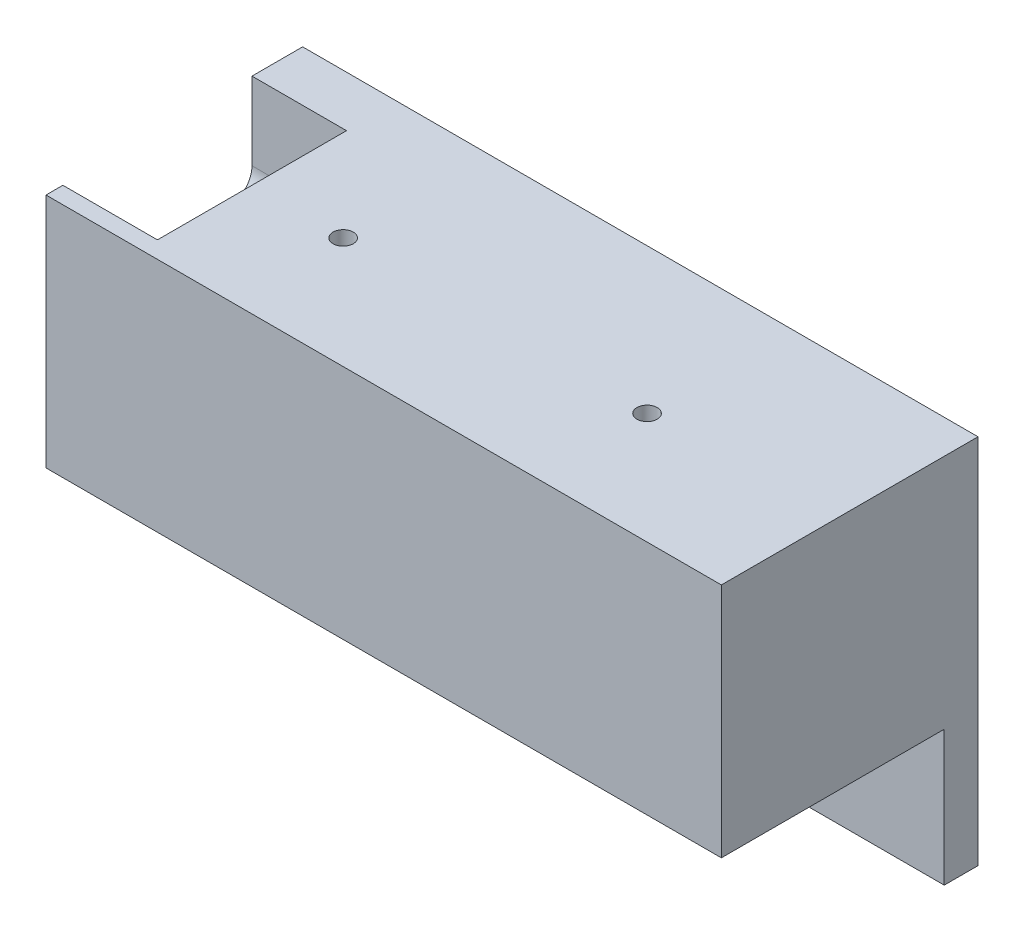
SolidWorks part; units mm, degrees
ref_plane "Ebene vorne" through (0, 0, 0) normal (0, 0, 1) x (1, 0, 0)
ref_plane "Ebene oben" through (0, 0, 0) normal (0, 1, 0) x (1, 0, 0)
ref_plane "Ebene rechts" through (0, 0, 0) normal (1, 0, 0) x (0, 0, -1)
sketch "Skizze1" plane through (0, 0, 0) normal (0, 0, 1) x (1, 0, 0)
  line L1 (-50, 27.5) -> (50, 27.5)
  line L2 (-50, 27.5) -> (-50, -27.5)
  line L3 (-50, -27.5) -> (50, -27.5)
  line L4 (50, 27.5) -> (50, -27.5)
  point P4 (0, 27.5)
  point P6 (50, 0)
  dimension "D1" = 100
  dimension "D2" = 55
extrude "Aufsatz-Linear austragen1" add sketch "Skizze1" along normal blind 38
sketch "Skizze2" plane through (0, 0, 38) normal (0, 0, 1) x (1, 0, 0)
  line L0 (50, -27.5) -> (50, 27.5) construction
  line L1 (-50, -27.5) -> (50, -27.5)
  line L2 (-50, -27.5) -> (-50, -7.5)
  line L3 (-50, -7.5) -> (50, -7.5)
  line L4 (50, -27.5) -> (50, -7.5)
  line L5 (50, 27.5) -> (-50, 27.5) construction
  dimension "D1" = 35
extrude "Schnitt-Linear austragen1" cut sketch "Skizze2" against normal blind 33
sketch "Skizze4" plane through (0, 0, 5) normal (0, 0, 1) x (1, 0, 0)
  line L0 (-50, -27.5) -> (50, -27.5) construction
  circle A0 centre (-10, -19.5) radius 1.5
  circle A1 centre (10, -19.5) radius 1.5
  dimension "D1" = 3
  dimension "D2" = 20
  dimension "D3" = 10
  dimension "D4" = 8
extrude "Schnitt-Linear austragen2" cut sketch "Skizze4" against normal through all
sketch "Skizze5" plane through (0, -7.5, 0) normal (0, -1, 0) x (1, 0, 0)
  line L0 (-50, 5) -> (-50, 38) construction
  line L1 (-46, 35.5) -> (46, 35.5)
  line L2 (-46, 35.5) -> (-46, 7.5)
  line L3 (-46, 7.5) -> (46, 7.5)
  line L4 (46, 35.5) -> (46, 7.5)
  point P4 (-46, 21.5)
  point P7 (-50, 21.5)
  point P8 (0, 35.5)
  dimension "D1" = 28
  dimension "D2" = 92
extrude "Schnitt-Linear austragen3" cut sketch "Skizze5" against normal blind 30
sketch "Skizze6" plane through (0, 22.5, 0) normal (0, -1, 0) x (1, 0, 0)
  line L0 (46, 7.5) -> (46, 35.5) construction
  circle A0 centre (-22.5, 21.5) radius 1.5
  circle A1 centre (22.5, 21.5) radius 1.5
  point P9 (46, 21.5)
  dimension "D3" = 3
  dimension "D1" = 45
  dimension "D2" = 22.5
extrude "Schnitt-Linear austragen4" cut sketch "Skizze6" against normal through all
fillet "Verrundung1" radius 3.5 4 edges at (-46, 7.5, 35.5) (46, 7.5, 35.5) (46, 7.5, 7.5) (-46, 7.5, 7.5)
sketch "Skizze7" plane through (-50, 0, 0) normal (-1, 0, 0) x (0, 0, 1)
  line L1 (7.5, 27.5) -> (35.5, 27.5)
  line L2 (7.5, 27.5) -> (7.5, 12.5)
  line L3 (7.5, 12.5) -> (35.5, 12.5)
  line L4 (35.5, 27.5) -> (35.5, 12.5)
  line L6 (7.5, 22.5) -> (7.5, -7.5) construction
  line L7 (35.5, -7.5) -> (35.5, 22.5) construction
  line L9 (38, 27.5) -> (0, 27.5) construction
  dimension "D1" = 15
extrude "Schnitt-Linear austragen5" cut sketch "Skizze7" against normal blind 14
fillet "Verrundung5" radius 3.5 2 edges at (-46.25, 12.5, 35.5) (-46.25, 12.5, 7.5)
